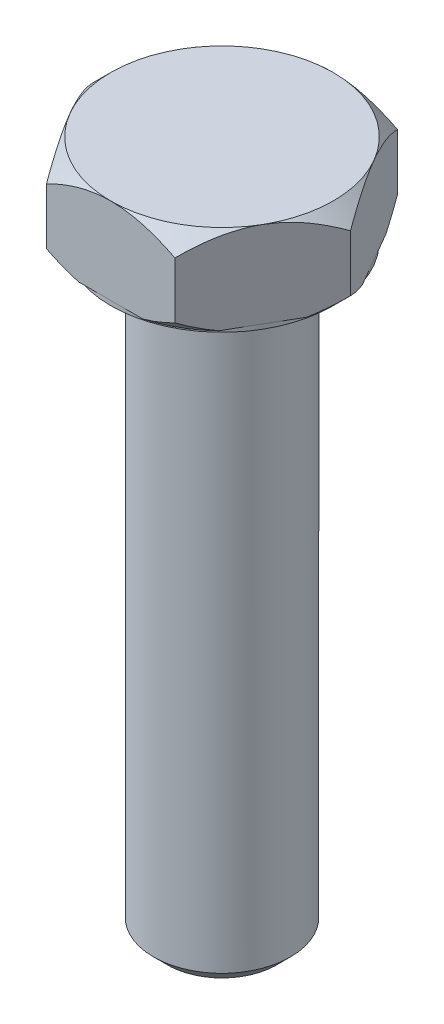
SolidWorks part; units mm, degrees
material "Cast Stainless Steel"
ref_plane "Front Plane" through (0, 0, 0) normal (0, 0, 1) x (1, 0, 0)
ref_plane "Top Plane" through (0, 0, 0) normal (0, 1, 0) x (1, 0, 0)
ref_plane "Right Plane" through (0, 0, 0) normal (1, 0, 0) x (0, 0, -1)
sketch "Sketch1" plane through (0, 0, 0) normal (0, 1, 0) x (1, 0, 0)
  line L0 (0, 0) -> (7.5056, 0) construction
  line L1 (7.5056, 0) -> (3.7528, 6.5)
  line L2 (3.7528, 6.5) -> (-3.7528, 6.5)
  line L3 (-3.7528, 6.5) -> (-7.5056, 0)
  line L4 (-7.5056, 0) -> (-3.7528, -6.5)
  line L5 (-3.7528, -6.5) -> (3.7528, -6.5)
  line L6 (3.7528, -6.5) -> (7.5056, 0)
  circle A0 centre (0, 0) radius 6.5 construction
  dimension "D1" = 13
extrude "Boss-Extrude1" add sketch "Sketch1" against normal blind 5.3
sketch "Sketch4" plane through (0, 0, 0) normal (1, 0, 0) x (0, 0, -1)
  line L0 (-6.5, 0) -> (-8.15, 0)
  line L1 (-8.15, 0) -> (-8.15, -1.65)
  line L2 (-8.15, -1.65) -> (-6.5, 0)
  line L3 (-6.5, -2.65) -> (6.5, -2.65) construction
  line L4 (-8.15, -3.65) -> (-6.5, -5.3)
  line L5 (-8.15, -5.3) -> (-8.15, -3.65)
  line L6 (-6.5, -5.3) -> (-8.15, -5.3)
  line L7 (0, 0) -> (0, -2.65) construction
  dimension "D1" = 45
  dimension "D2" = 2.65
  dimension "D3" = 1.65
  dimension "D4" = 13
revolve "Cut-Revolve1" cut sketch "Sketch4" angle 360 about L7
sketch "Sketch2" plane through (0, -5.3, 0) normal (0, -1, 0) x (1, 0, 0)
  circle A0 centre (0, 0) radius 6.5
  dimension "D1" = 13
extrude "Cut-Extrude1" cut sketch "Sketch2" against normal blind 0.265 flip side to cut
sketch "Sketch3" plane through (0, -5.3, 0) normal (0, -1, 0) x (1, 0, 0)
  circle A0 centre (0, 0) radius 4
  dimension "D1" = 8
extrude "Boss-Extrude2" add sketch "Sketch3" along normal blind 35
chamfer "Chamfer1" distance 0.8 angle 45 1 edges at (0, -40.3, -4)
equation "\"k\"= 5.3"
equation "\"e\"= 14.38"
equation "\"S\"= 13"
equation "\"L\"= 35"
equation "\"D1@Sketch1\"=\"S\""
equation "\"D1@Boss-Extrude1\"=\"k\""
equation "\"D1@Sketch2\"=\"S\""
equation "\"D1@Cut-Extrude1\"=\"k\"/20"
equation "\"d\"= 8"
equation "\"D1@Sketch3\"=\"d\""
equation "\"D1@Boss-Extrude2\"=\"L\""
equation "\"D2@Sketch4\"=\"k\"/2"
equation "\"D3@Sketch4\"=\"D2@Sketch4\"-1"
equation "\"D4@Sketch4\"=\"S\""
equation "\"D1@Chamfer1\"=\"d\"/10"
